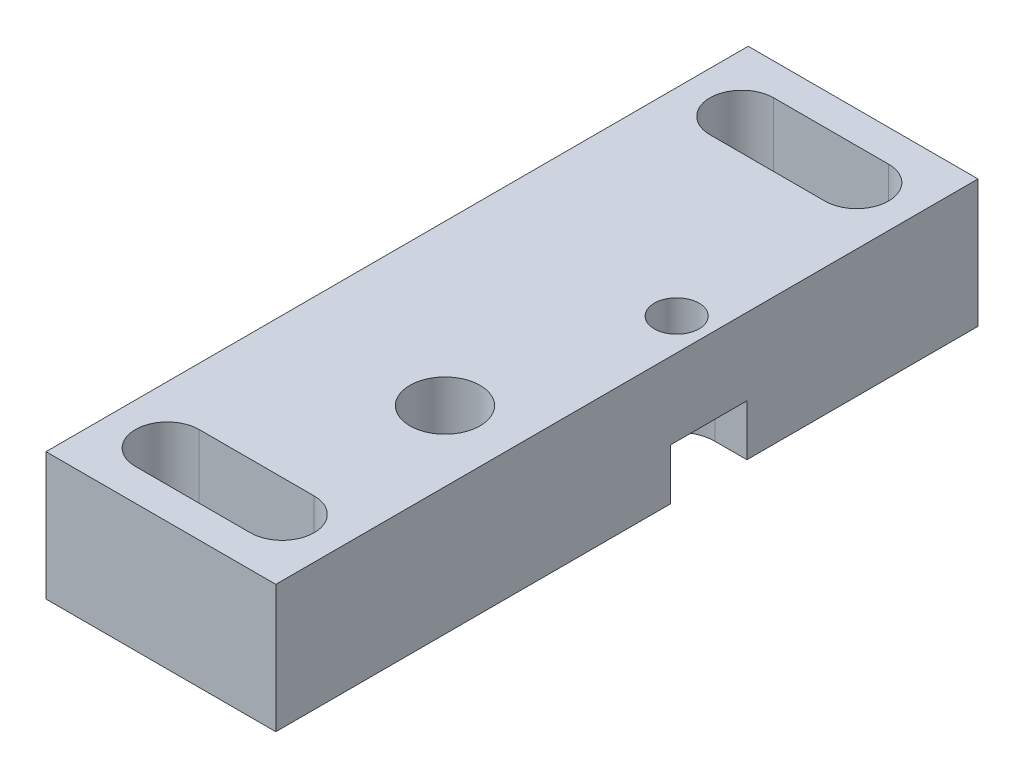
SolidWorks part; units mm, degrees
ref_plane "Front Plane" through (0, 0, 0) normal (0, 0, 1) x (1, 0, 0)
ref_plane "Top Plane" through (0, 0, 0) normal (0, 1, 0) x (1, 0, 0)
ref_plane "Right Plane" through (0, 0, 0) normal (1, 0, 0) x (0, 0, -1)
sketch "Sketch1" plane through (0, 0, 0) normal (0, 1, 0) x (1, 0, 0)
  line L1 (-9, 27.5) -> (9, 27.5)
  line L2 (-9, 27.5) -> (-9, -27.5)
  line L3 (-9, -27.5) -> (9, -27.5)
  line L4 (9, 27.5) -> (9, -27.5)
  line L5 (-9, 27.5) -> (9, -27.5) construction
  line L6 (-9, -27.5) -> (9, 27.5) construction
  point P0 (0, 0)
  dimension "D1" = 18
  dimension "D2" = 55
extrude "Boss-Extrude1" add sketch "Sketch1" along normal blind 10
sketch "Sketch2" plane through (0, 10, 0) normal (0, 1, 0) x (1, 0, 0)
  line L0 (3.5, -8.75) -> (3.5, -11.5) construction
  line L1 (3.5, -11.5) -> (3.5, -27.5) construction
  line L2 (-9, -27.5) -> (9, -27.5) construction
  line L3 (3.5, -8.75) -> (6.25, -8.75) construction
  line L4 (6.25, -8.75) -> (9, -8.75) construction
  line L5 (9, -27.5) -> (9, 27.5) construction
  line L6 (6.5, 6.4) -> (6.5, 8.15) construction
  line L7 (6.5, 8.15) -> (6.5, 27.5) construction
  line L8 (9, 27.5) -> (-9, 27.5) construction
  line L9 (6.5, 6.4) -> (8.25, 6.4) construction
  line L10 (8.25, 6.4) -> (9, 6.4) construction
  circle A0 centre (3.5, -8.75) radius 2.75
  circle A1 centre (6.5, 6.4) radius 1.75
  dimension "D1" = 3.5
  dimension "D2" = 5.5
  dimension "D3" = 2.75
  dimension "D4" = 16
  dimension "D5" = 19.35
  dimension "D6" = 0.75
extrude "Cut-Extrude1" cut sketch "Sketch2" against normal through all
sketch "Sketch3" plane through (0, 0, 0) normal (0, -1, 0) x (1, 0, 0)
  circle A0 centre (3.5, 8.75) radius 4.75
  dimension "D1" = 9.5
extrude "Cut-Extrude2" cut sketch "Sketch3" against normal blind 5.5
sketch "Sketch4" plane through (0, 0, 0) normal (0, -1, 0) x (1, 0, 0)
  line L0 (6.5, -9.4) -> (9, -9.4)
  line L1 (9, 27.5) -> (9, -27.5) construction
  line L2 (9, -9.4) -> (9, -3.4)
  line L3 (9, -3.4) -> (6.5, -3.4)
  circle A0 centre (6.5, -6.4) radius 3
  circle M2 centre (6.5, -6.4) radius 1.75
  line M3 (9, -27.5) -> (9, 27.5)
  dimension "D1" = 6
extrude "Cut-Extrude3" cut sketch "Sketch4" against normal blind 4 contours A0 L2 M2 | A0 L0 M3 | A0 L3 M3
sketch "Sketch5" plane through (0, 0, 0) normal (0, 1, 0) x (1, 0, 0)
  line L0 (-7, 22.5) -> (-4.5, 22.5) construction
  line L1 (-4.5, 22.5) -> (4.5, 22.5) construction
  line L2 (4.5, 22.5) -> (7, 22.5) construction
  line L3 (-4.5, 25) -> (4.5, 25)
  line L4 (4.5, 20) -> (-4.5, 20)
  line L5 (0, -22.5) -> (0, 22.5) construction
  line L6 (-9, 0) -> (9, 0) construction
  line L7 (-9, 27.5) -> (-9, -27.5) construction
  line L8 (9, -27.5) -> (9, 27.5) construction
  line L9 (9, 27.5) -> (-9, 27.5) construction
  line L10 (4.5, -22.5) -> (7, -22.5) construction
  line L11 (-4.5, -22.5) -> (4.5, -22.5) construction
  line L12 (-7, -22.5) -> (-4.5, -22.5) construction
  line L13 (4.5, -20) -> (-4.5, -20)
  line L14 (-4.5, -25) -> (4.5, -25)
  circle A0 centre (-4.5, 22.5) radius 2.5
  circle A1 centre (4.5, 22.5) radius 2.5
  circle A2 centre (4.5, -22.5) radius 2.5
  circle A3 centre (-4.5, -22.5) radius 2.5
  point P23 (0, 0)
  dimension "D1" = 5
  dimension "D2" = 14
  dimension "D3" = 2.5
extrude "Cut-Extrude4" cut sketch "Sketch5" along normal through all contours A0 | A1 L3 A0 L4 | A1 | A3 | L13 A3 L14 A2 | A2
